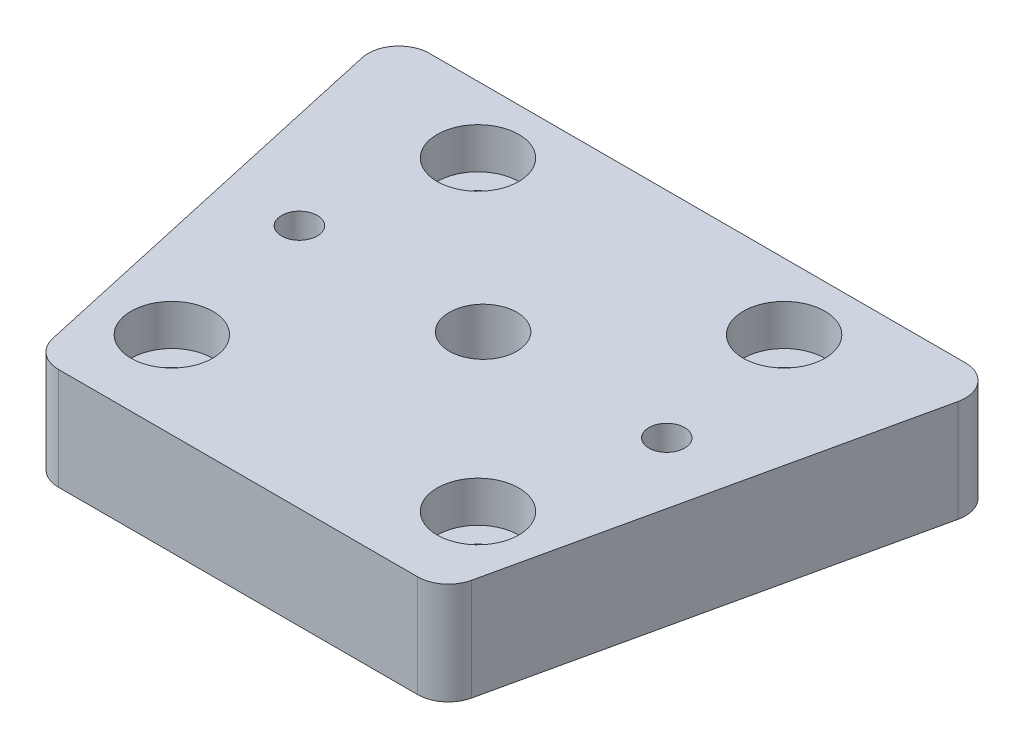
SolidWorks part; units mm, degrees
ref_plane "Front Plane" through (0, 0, 0) normal (0, 0, 1) x (1, 0, 0)
ref_plane "Top Plane" through (0, 0, 0) normal (0, 1, 0) x (1, 0, 0)
ref_plane "Right Plane" through (0, 0, 0) normal (1, 0, 0) x (0, 0, -1)
sketch "Sketch1" plane through (0, 0, 0) normal (0, 1, 0) x (1, 0, 0)
  line L0 (0, 0) -> (10, -45)
  line L1 (10, -45) -> (50, -45)
  line L2 (50, -45) -> (60, 0)
  line L3 (60, 0) -> (0, 0)
  line L4 (30, 0) -> (30, -45) construction
  dimension "D1" = 60
  dimension "D2" = 40
  dimension "D3" = 45
extrude "Boss-Extrude2" add sketch "Sketch1" along normal blind 10
sketch "Sketch4" plane through (0, 10, 0) normal (0, 1, 0) x (1, 0, 0)
  line L0 (30, 0) -> (30, -45) construction
  line L1 (60, 0) -> (0, 0) construction
  line L2 (10, -45) -> (50, -45) construction
  line L3 (30, -22.5) -> (55, -22.5) construction
  line L4 (50, -45) -> (60, 0) construction
  line L5 (30, -22.5) -> (5, -22.5) construction
  line L6 (0, 0) -> (10, -45) construction
  circle A0 centre (15, -6.5) radius 4
  circle A1 centre (45, -6.5) radius 4
  circle A2 centre (45, -36.5) radius 4
  circle A3 centre (15, -36.5) radius 4
  dimension "D1" = 8
  dimension "D2" = 8
  dimension "D3" = 8
  dimension "D4" = 8
  dimension "D5" = 15
  dimension "D6" = 14
  dimension "D7" = 16
  dimension "D8" = 15
extrude "Cut-Extrude1" cut sketch "Sketch4" against normal blind 4
fillet "Fillet1" radius 3 4 edges at (0, 5, 0) (10, 5, 45) (50, 5, 45) (60, 5, 0)
sketch "Sketch5" plane through (0, 0, 0) normal (0, -1, 0) x (1, 0, 0)
  line L0 (30, 45) -> (30, 0) construction
  line L1 (12.4065, 45) -> (47.5935, 45) construction
  line L2 (56.2602, 0) -> (3.7398, 0) construction
  line L3 (12, 21) -> (48, 21) construction
  circle A0 centre (12, 21) radius 1.75
  circle A1 centre (48, 21) radius 1.75
  circle A2 centre (30, 21) radius 3.31
  dimension "D1" = 3.5
  dimension "D2" = 3.5
  dimension "D5" = 6.62
  dimension "D3" = 18
  dimension "D4" = 21
extrude "Cut-Extrude2" cut sketch "Sketch5" against normal up to surface (10 mm away) up to face at (15, 10, 40.5)
sketch "Sketch7" plane through (0, 10, 0) normal (0, 1, 0) x (1, 0, 0)
  circle A0 centre (15, -6.5) radius 1.75
  circle A1 centre (45, -6.5) radius 1.75
  circle A2 centre (45, -36.5) radius 1.75
  circle A3 centre (15, -36.5) radius 1.75
  dimension "D1" = 3.5
  dimension "D2" = 3.5
  dimension "D3" = 3.5
  dimension "D4" = 3.5
extrude "Cut-Extrude3" cut sketch "Sketch7" against normal up to surface (10 mm away) up to face at (12, 0, 19.25)
sketch "Sketch8" plane through (0, 0, 0) normal (0, -1, 0) x (1, 0, 0)
  circle A0 centre (15, 36.5) radius 3.5
  circle A1 centre (45, 36.5) radius 3.5
  circle A2 centre (45, 6.5) radius 3.5
  circle A3 centre (15, 6.5) radius 3.5
  dimension "D1" = 7
  dimension "D2" = 7
  dimension "D3" = 7
  dimension "D4" = 7
extrude "Cut-Extrude4" cut sketch "Sketch8" against normal blind 3
